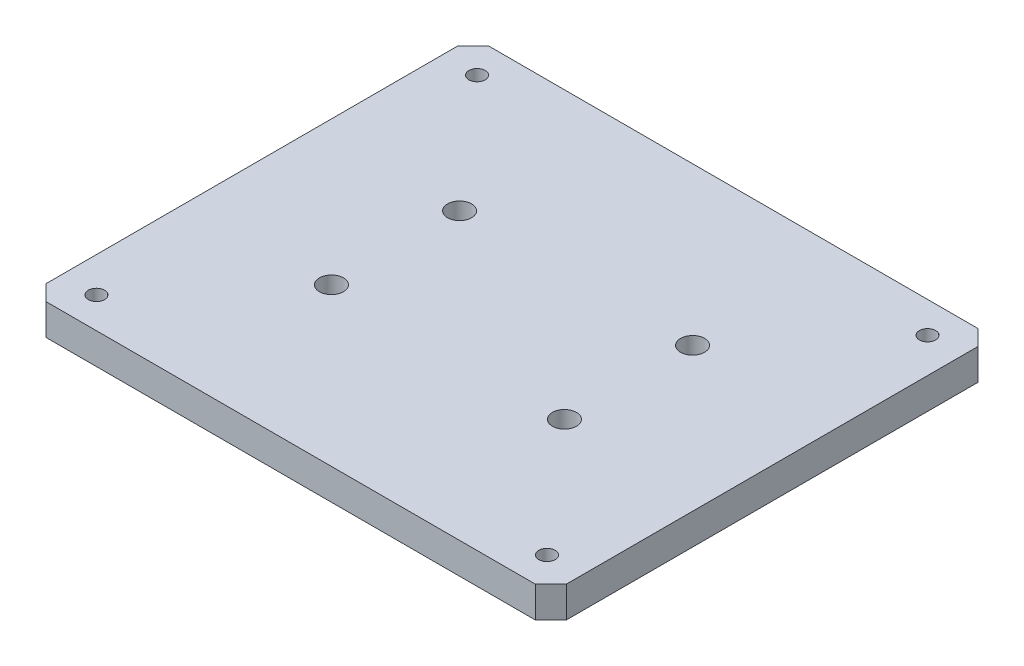
SolidWorks part; units mm, degrees
ref_plane "Front Plane" through (0, 0, 0) normal (0, 0, 1) x (1, 0, 0)
ref_plane "Top Plane" through (0, 0, 0) normal (0, 1, 0) x (1, 0, 0)
ref_plane "Right Plane" through (0, 0, 0) normal (1, 0, 0) x (0, 0, -1)
sketch "Sketch1" plane through (0, 0, 0) normal (0, 1, 0) x (1, 0, 0)
  line L0 (-36.1269, 0) -> (35.9266, 0) construction
  line L1 (-15, 8.25) -> (15, 8.25) construction
  line L2 (-15, 8.25) -> (-15, -8.25) construction
  line L3 (-15, -8.25) -> (15, -8.25) construction
  line L4 (15, 8.25) -> (15, -8.25) construction
  line L5 (-15, 8.25) -> (15, -8.25) construction
  line L6 (-15, -8.25) -> (15, 8.25) construction
  line L7 (-33.5, 28.5) -> (33.5, 28.5)
  line L8 (-33.5, 28.5) -> (-33.5, -28.5)
  line L9 (-33.5, -28.5) -> (33.5, -28.5)
  line L10 (33.5, 28.5) -> (33.5, -28.5)
  line L11 (-33.5, 28.5) -> (33.5, -28.5) construction
  line L12 (-33.5, -28.5) -> (33.5, 28.5) construction
  line L13 (0, 29.3515) -> (0, -31.773) construction
  circle A0 centre (15, 8.25) radius 1.55
  circle A1 centre (-15, 8.25) radius 1.55
  circle A2 centre (-15, -8.25) radius 1.55
  circle A3 centre (15, -8.25) radius 1.55
  point P0 (0, 0)
  point P5 (0, 0)
  dimension "D5" = 3.1
  dimension "D1" = 30
  dimension "D2" = 16.5
  dimension "D3" = 67
  dimension "D4" = 57
extrude "Boss-Extrude1" add sketch "Sketch1" along normal blind 4
sketch "Sketch2" plane through (0, 4, 0) normal (0, 1, 0) x (1, 0, 0)
  line L0 (-42.6226, 0) -> (56.5461, 0) construction
  line L1 (0, 39.6665) -> (0, -39.3531) construction
  circle A0 centre (29, 24.5) radius 1.05
  circle A1 centre (-29, 24.5) radius 1.05
  circle A2 centre (-29, -24.5) radius 1.05
  circle A3 centre (29, -24.5) radius 1.05
  dimension "D1" = 2.1
  dimension "D2" = 29
  dimension "D3" = 24.5
extrude "Cut-Extrude1" cut sketch "Sketch2" against normal through all
chamfer "Chamfer1" distance 2 angle 45 4 edges at (-33.5, 2, 28.5) (33.5, 2, 28.5) (33.5, 2, -28.5) (-33.5, 2, -28.5)
